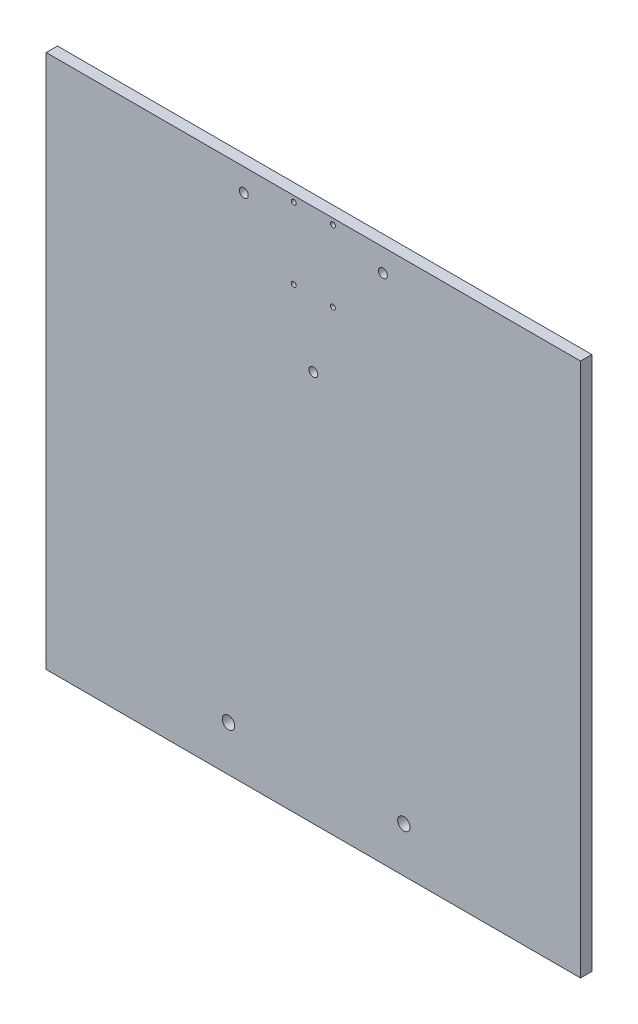
SolidWorks part; units mm, degrees
ref_plane "Front Plane" through (0, 0, 0) normal (0, 0, 1) x (1, 0, 0)
ref_plane "Top Plane" through (0, 0, 0) normal (0, 1, 0) x (1, 0, 0)
ref_plane "Right Plane" through (0, 0, 0) normal (1, 0, 0) x (0, 0, -1)
sketch "Sketch1" plane through (0, 0, 0) normal (0, 0, 1) x (1, 0, 0)
  line L1 (0, 0) -> (299.974, 0)
  line L2 (0, 0) -> (0, -299.974)
  line L3 (0, -299.974) -> (299.974, -299.974)
  line L4 (299.974, 0) -> (299.974, -299.974)
  dimension "D1" = 299.974
  dimension "D2" = 299.974
extrude "Boss-Extrude1" add sketch "Sketch1" along normal blind 6.35 contours L1 L4 L3 L2
ref_plane "Plane1" through (0, -149.987, 0) normal (0, -1, 0) x (-1, 0, 0)
ref_plane "Plane2" through (149.987, 0, 0) normal (-1, 0, 0) x (0, 0, 1)
sketch "Sketch3" plane through (0, 0, 0) normal (0, 0, -1) x (-1, 0, 0)
  circle A8 centre (-160.987, -3.25) radius 1.375
  circle A9 centre (-138.987, -3.25) radius 1.375
  circle A10 centre (-138.987, -43.25) radius 1.375
  circle A11 centre (-160.987, -43.25) radius 1.375
  dimension "D1" = 2.75
extrude "Cut-Extrude1" cut sketch "Sketch3" against normal through all
sketch "Sketch4" plane through (0, 0, 0) normal (0, 0, -1) x (-1, 0, 0)
  circle A0 centre (-189.0315, -12.7076) radius 2.5
  circle A1 centre (-110.9425, -12.7076) radius 2.5
  circle A2 centre (-149.987, -80.3348) radius 2.5
  dimension "D1" = 5
  dimension "D2" = 5
  dimension "D3" = 5
extrude "Cut-Extrude2" cut sketch "Sketch4" against normal through all
sketch "Sketch5" plane through (0, 0, 6.35) normal (0, 0, 1) x (1, 0, 0)
  circle A0 centre (200.787, -274.574) radius 3.4925
  circle A1 centre (102.362, -274.574) radius 3.4925
  dimension "D1" = 6.985
extrude "Cut-Extrude3" cut sketch "Sketch5" against normal through all
equation "\"D2@Sketch4\"=\"D1@Sketch4\""
equation "\"D3@Sketch4\"=\"D1@Sketch4\""
